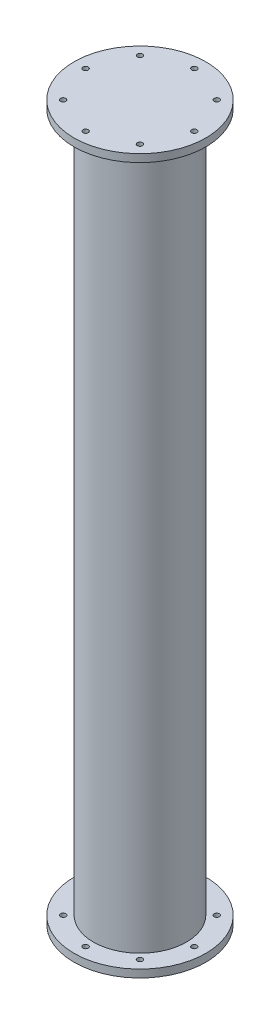
SolidWorks part; units mm, degrees
material "7075-O (SS)"
ref_plane "Front" through (0, 0, 0) normal (0, 0, 1) x (1, 0, 0)
ref_plane "Top" through (0, 0, 0) normal (0, 1, 0) x (1, 0, 0)
ref_plane "Right" through (0, 0, 0) normal (1, 0, 0) x (0, 0, -1)
sketch "Croquis1" plane through (0, 0, 0) normal (0, 1, 0) x (1, 0, 0)
  circle A0 centre (0, 0) radius 30
  circle A1 centre (0, 0) radius 25
  dimension "DE" = 60
  dimension "DI" = 50
extrude "Saliente-Extruir1" add sketch "Croquis1" along normal mid plane 450
sketch "Croquis2" plane through (0, 225, 0) normal (0, 1, 0) x (1, 0, 0)
  line L0 (0, 42.5) -> (0, 32.7) construction
  circle A0 centre (0, 0) radius 42.5
  dimension "D1" = 85
extrude "Saliente-Extruir2" add sketch "Croquis2" along normal blind 5
hole_wizard "Taladro de margen para M31" positions "Croquis3" profile "Croquis4" hole size "M3" standard "Ansi Metric" end condition up to next
sketch "Croquis3" plane through (0, 225, 0) normal (0, -1, 0) x (-1, 0, 0)
  line L3 (0, 46.75) -> (0, -46.75) construction
  circle A0 centre (0, 0) radius 35 construction
  point P13 (-24.7487, -24.7487)
  point P21 (-35, 0)
  point P22 (-24.7487, 24.7487)
  point P23 (0, 35)
  point P24 (24.7487, 24.7487)
  point P25 (35, 0)
  point P34 (24.7487, -24.7487)
  point P35 (0, -35)
  point P40 (0, 0)
  point P41 (22.6805, -32.9091)
  point P42 (3.1741, -34.8558)
  point P45 (12.1496, 32.8236)
  dimension "D1" = 70
  dimension "D2" = 8
sketch "Croquis4" plane through (0, 225, 35) normal (1, 0, 0) x (0, 0, -1)
  line L0 (0, 0) -> (0, 5.001)
  line L1 (0, 5.001) -> (1.7, 5.001)
  line L2 (1.7, 5.001) -> (1.7, 0)
  line L5 (1.7, 0) -> (0, 0)
  line L11 (0, -6.35) -> (0, 107.95) construction
  dimension "Diámetro de taladro hasta el siguiente" = 3.4
  dimension "Profundidad de taladro hasta el siguiente" = 5.001
mirror "Simetría1" about plane through (0, 0, 0) normal (0, 1, 0) of "Taladro de margen para M31", "Saliente-Extruir2"
